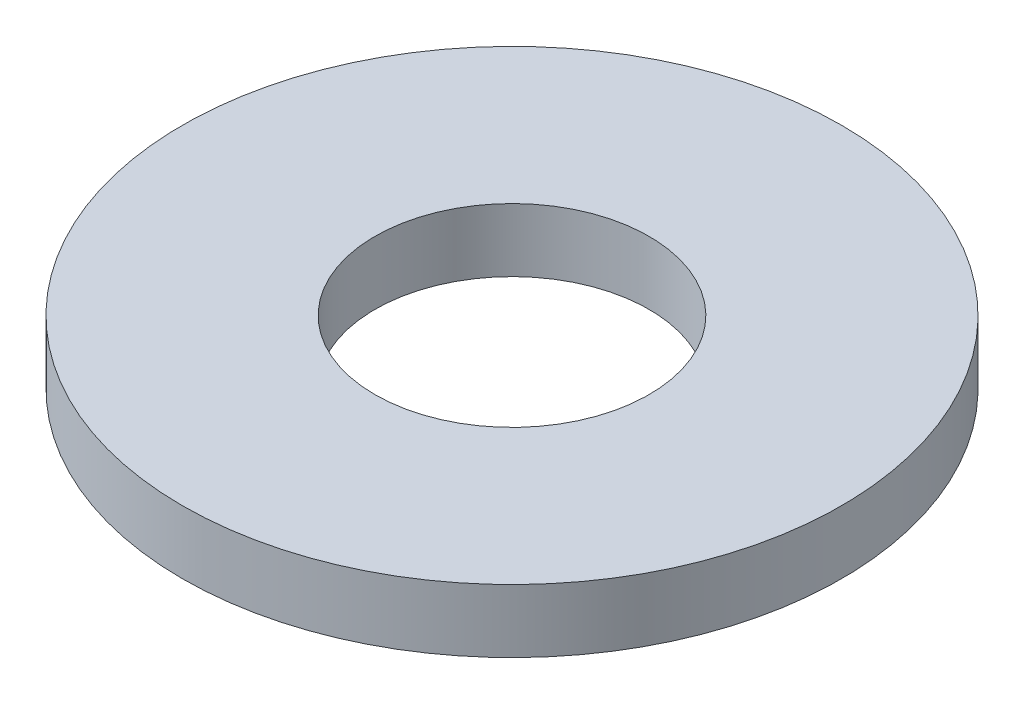
SolidWorks part; units mm, degrees
ref_plane "Front Plane" through (0, 0, 0) normal (0, 0, 1) x (1, 0, 0)
ref_plane "Top Plane" through (0, 0, 0) normal (0, 1, 0) x (1, 0, 0)
ref_plane "Right Plane" through (0, 0, 0) normal (1, 0, 0) x (0, 0, -1)
sketch "Sketch1" plane through (0, 0, 0) normal (0, 1, 0) x (1, 0, 0)
  circle A0 centre (0, 0) radius 9.525
  dimension "OD" = 19.05
extrude "Boss-Extrude1" add sketch "Sketch1" along normal blind 1.8288
sketch "Sketch5" plane through (0, 1.8288, 0) normal (0, 1, 0) x (-1, 0, 0)
  circle A0 centre (0, 0) radius 3.9624
  dimension "ID" = 7.9248
extrude "Cut-Extrude1" cut sketch "Sketch5" against normal through all
